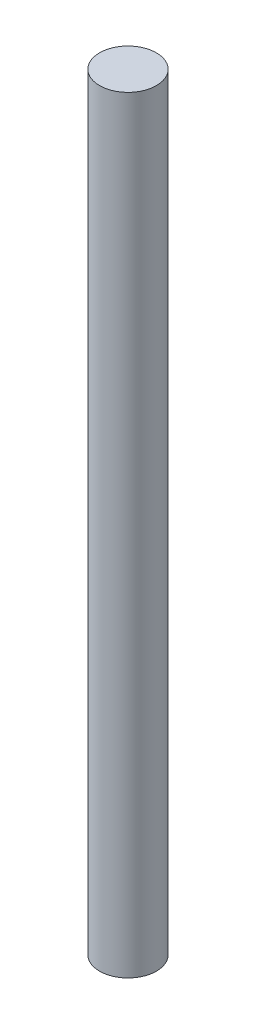
SolidWorks part; units mm, degrees
ref_plane "Front Plane" through (0, 0, 0) normal (0, 0, 1) x (1, 0, 0)
ref_plane "Top Plane" through (0, 0, 0) normal (0, 1, 0) x (1, 0, 0)
ref_plane "Right Plane" through (0, 0, 0) normal (1, 0, 0) x (0, 0, -1)
sketch "Sketch1" plane through (0, 0, 0) normal (0, 1, 0) x (1, 0, 0)
  circle A0 centre (0, 0) radius 11.1125
  dimension "D1" = 22.225
extrude "Boss-Extrude1" add sketch "Sketch1" along normal blind 300
